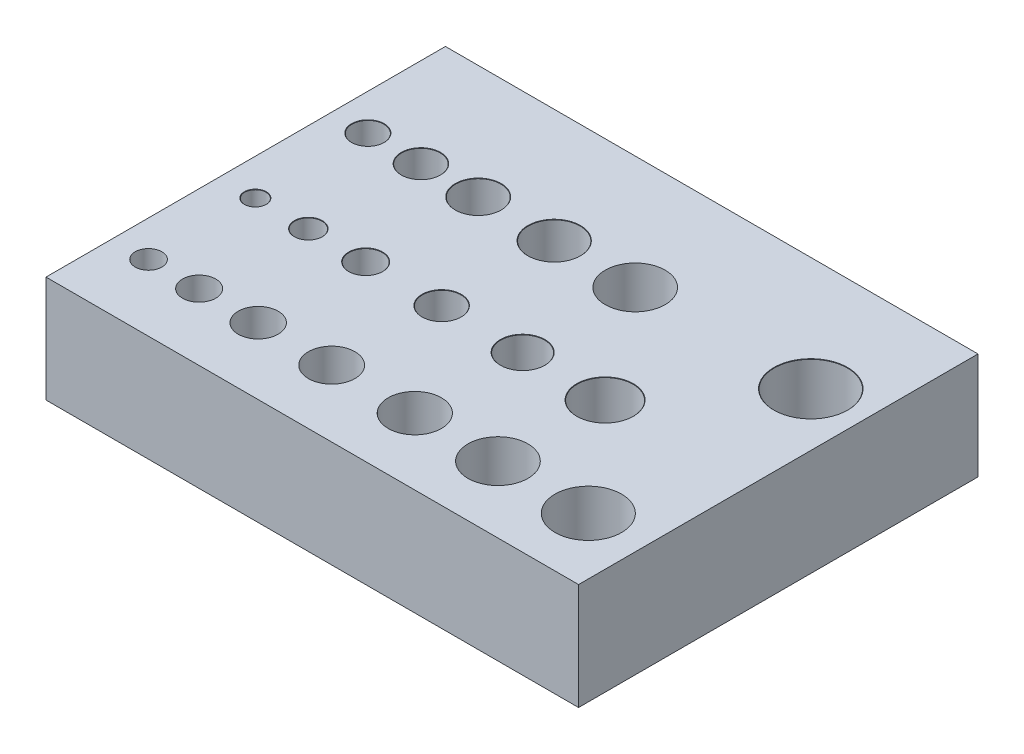
SolidWorks part; units mm, degrees
ref_plane "Front Plane" through (0, 0, 0) normal (0, 0, 1) x (1, 0, 0)
ref_plane "Top Plane" through (0, 0, 0) normal (0, 1, 0) x (1, 0, 0)
ref_plane "Right Plane" through (0, 0, 0) normal (1, 0, 0) x (0, 0, -1)
sketch "Sketch1" plane through (0, 0, 0) normal (0, 1, 0) x (1, 0, 0)
  line L0 (0, 5) -> (40, 5) construction
  line L1 (0, 0) -> (40, 0)
  line L2 (0, 0) -> (0, 30)
  line L3 (0, 30) -> (40, 30)
  line L4 (40, 0) -> (40, 30)
  line L5 (0, 12.8995) -> (40, 12.8995) construction
  circle A0 centre (2.7023, 5) radius 1
  circle A1 centre (6.5026, 5) radius 1.25
  circle A2 centre (10.9365, 5) radius 1.5
  circle A3 centre (16.457, 5) radius 1.75
  circle A4 centre (22.7004, 5) radius 2
  circle A5 centre (28.946, 5) radius 2.25
  circle A6 centre (35.7324, 5) radius 2.5
  point P19 (2.7023, 12.8995)
  point P22 (6.5026, 12.8995)
  point P23 (10.9365, 12.8995)
  point P24 (16.457, 12.8995)
  point P27 (22.7004, 12.8995)
  point P28 (28.946, 12.8995)
  point P29 (35.7324, 12.8995)
  dimension "D3" = 2
  dimension "D4" = 2.5
  dimension "D5" = 3
  dimension "D6" = 3.5
  dimension "D7" = 4
  dimension "D8" = 4.5
  dimension "D10" = 5
  dimension "D1" = 30
  dimension "D2" = 40
  dimension "D9" = 5
extrude "Boss-Extrude1" add sketch "Sketch1" along normal blind 8
sketch "Sketch2" plane through (0, 8, 0) normal (0, 1, 0) x (1, 0, 0)
  line L0 (0, 13) -> (40, 13) construction
  line L1 (0, 30) -> (0, 0) construction
  line L2 (40, 0) -> (40, 30) construction
  line L3 (0, 0) -> (40, 0) construction
  line L4 (0, 21.4534) -> (40, 21.4534) construction
  point P6 (2.7202, 13)
  point P7 (6.7037, 13)
  point P8 (11.0102, 13)
  point P9 (16.7163, 13)
  point P10 (22.7992, 13)
  point P11 (28.9898, 13)
  point P12 (35.9878, 13)
  point P17 (2.7202, 21.4534)
  point P18 (6.7037, 21.4534)
  point P19 (11.0102, 21.4534)
  point P20 (16.7163, 21.4534)
  point P21 (22.7992, 21.4534)
  point P22 (28.9898, 21.4534)
  point P23 (35.9878, 21.4534)
  dimension "D1" = 13
hole_wizard "Tap Drill for M2x0.4 Tap1" positions "Sketch3" profile "Sketch4" hole size "M2x0.4" standard "ANSI Metric" end condition through all
sketch "Sketch3" plane through (0, 8, 0) normal (0, 1, 0) x (1, 0, 0)
  point P0 (2.7202, 13)
sketch "Sketch4" plane through (2.7202, 8, -13) normal (1, 0, 0) x (0, 0, 1)
  line L0 (0, 0) -> (0, 8)
  line L1 (0, 8) -> (0.825, 8)
  line L2 (0.8, 7.975) -> (0.8, 0.025)
  line L3 (0.8, 0.025) -> (0.825, 0)
  line L5 (0.825, 0) -> (0, 0)
  line L6 (-0.8, 0.025) -> (-0.825, 0) construction
  line L7 (0.825, 8) -> (0.8, 7.975)
  line L8 (-0.825, 8) -> (-0.8, 7.975) construction
  line L11 (0, -6.35) -> (0, 107.95) construction
  dimension "Thru Hole Dia." = 1.6
  dimension "Thru Hole Depth" = 8
  dimension "Near C'Sink Dia." = 1.65
  dimension "Near C'Sink Angle" = 90
  dimension "Far C'Sink Dia." = 1.65
  dimension "Far C'Sink Angle" = 90
hole_wizard "Tap Drill for M2.5x0.45 Tap1" positions "Sketch5" profile "Sketch6" hole size "M2.5x0.45" standard "ANSI Metric" end condition through all
sketch "Sketch5" plane through (0, 8, 0) normal (0, 1, 0) x (1, 0, 0)
  point P0 (6.7037, 13)
sketch "Sketch6" plane through (6.7037, 8, -13) normal (1, 0, 0) x (0, 0, 1)
  line L0 (0, 0) -> (0, 8)
  line L1 (0, 8) -> (1.05, 8)
  line L2 (1.025, 7.975) -> (1.025, 0.025)
  line L3 (1.025, 0.025) -> (1.05, 0)
  line L5 (1.05, 0) -> (0, 0)
  line L6 (-1.025, 0.025) -> (-1.05, 0) construction
  line L7 (1.05, 8) -> (1.025, 7.975)
  line L8 (-1.05, 8) -> (-1.025, 7.975) construction
  line L11 (0, -6.35) -> (0, 107.95) construction
  dimension "Thru Hole Dia." = 2.05
  dimension "Thru Hole Depth" = 8
  dimension "Near C'Sink Dia." = 2.1
  dimension "Near C'Sink Angle" = 90
  dimension "Far C'Sink Dia." = 2.1
  dimension "Far C'Sink Angle" = 90
hole_wizard "Tap Drill for M3x0.5 Tap1" positions "Sketch7" profile "Sketch8" hole size "M3x0.5" standard "ANSI Metric" end condition through all
sketch "Sketch7" plane through (0, 8, 0) normal (0, 1, 0) x (1, 0, 0)
  point P0 (11.0102, 13)
sketch "Sketch8" plane through (11.0102, 8, -13) normal (1, 0, 0) x (0, 0, 1)
  line L0 (0, 0) -> (0, 8)
  line L1 (0, 8) -> (1.275, 8)
  line L2 (1.25, 7.975) -> (1.25, 0.025)
  line L3 (1.25, 0.025) -> (1.275, 0)
  line L5 (1.275, 0) -> (0, 0)
  line L6 (-1.25, 0.025) -> (-1.275, 0) construction
  line L7 (1.275, 8) -> (1.25, 7.975)
  line L8 (-1.275, 8) -> (-1.25, 7.975) construction
  line L11 (0, -6.35) -> (0, 107.95) construction
  dimension "Thru Hole Dia." = 2.5
  dimension "Thru Hole Depth" = 8
  dimension "Near C'Sink Dia." = 2.55
  dimension "Near C'Sink Angle" = 90
  dimension "Far C'Sink Dia." = 2.55
  dimension "Far C'Sink Angle" = 90
hole_wizard "Tap Drill for M3.5x0.6 Tap1" positions "Sketch9" profile "Sketch10" hole size "M3.5x0.6" standard "ANSI Metric" end condition through all
sketch "Sketch9" plane through (0, 8, 0) normal (0, 1, 0) x (1, 0, 0)
  point P0 (16.7163, 13)
sketch "Sketch10" plane through (16.7163, 8, -13) normal (1, 0, 0) x (0, 0, 1)
  line L0 (0, 0) -> (0, 8)
  line L1 (0, 8) -> (1.475, 8)
  line L2 (1.45, 7.975) -> (1.45, 0.025)
  line L3 (1.45, 0.025) -> (1.475, 0)
  line L5 (1.475, 0) -> (0, 0)
  line L6 (-1.45, 0.025) -> (-1.475, 0) construction
  line L7 (1.475, 8) -> (1.45, 7.975)
  line L8 (-1.475, 8) -> (-1.45, 7.975) construction
  line L11 (0, -6.35) -> (0, 107.95) construction
  dimension "Thru Hole Dia." = 2.9
  dimension "Thru Hole Depth" = 8
  dimension "Near C'Sink Dia." = 2.95
  dimension "Near C'Sink Angle" = 90
  dimension "Far C'Sink Dia." = 2.95
  dimension "Far C'Sink Angle" = 90
hole_wizard "Tap Drill for M4x0.7 Tap1" positions "Sketch11" profile "Sketch12" hole size "M4x0.7" standard "ANSI Metric" end condition through all
sketch "Sketch11" plane through (0, 8, 0) normal (0, 1, 0) x (1, 0, 0)
  point P0 (22.7992, 13)
sketch "Sketch12" plane through (22.7992, 8, -13) normal (1, 0, 0) x (0, 0, 1)
  line L0 (0, 0) -> (0, 8)
  line L1 (0, 8) -> (1.675, 8)
  line L2 (1.65, 7.975) -> (1.65, 0.025)
  line L3 (1.65, 0.025) -> (1.675, 0)
  line L5 (1.675, 0) -> (0, 0)
  line L6 (-1.65, 0.025) -> (-1.675, 0) construction
  line L7 (1.675, 8) -> (1.65, 7.975)
  line L8 (-1.675, 8) -> (-1.65, 7.975) construction
  line L11 (0, -6.35) -> (0, 107.95) construction
  dimension "Thru Hole Dia." = 3.3
  dimension "Thru Hole Depth" = 8
  dimension "Near C'Sink Dia." = 3.35
  dimension "Near C'Sink Angle" = 90
  dimension "Far C'Sink Dia." = 3.35
  dimension "Far C'Sink Angle" = 90
hole_wizard "Tap Drill for M5x0.8 Tap1" positions "Sketch13" profile "Sketch14" hole size "M5x0.8" standard "ANSI Metric" end condition through all
sketch "Sketch13" plane through (0, 8, 0) normal (0, 1, 0) x (1, 0, 0)
  point P0 (28.9898, 13)
sketch "Sketch14" plane through (28.9898, 8, -13) normal (1, 0, 0) x (0, 0, 1)
  line L0 (0, 0) -> (0, 8)
  line L1 (0, 8) -> (2.125, 8)
  line L2 (2.1, 7.975) -> (2.1, 0.025)
  line L3 (2.1, 0.025) -> (2.125, 0)
  line L5 (2.125, 0) -> (0, 0)
  line L6 (-2.1, 0.025) -> (-2.125, 0) construction
  line L7 (2.125, 8) -> (2.1, 7.975)
  line L8 (-2.125, 8) -> (-2.1, 7.975) construction
  line L11 (0, -6.35) -> (0, 107.95) construction
  dimension "Thru Hole Dia." = 4.2
  dimension "Thru Hole Depth" = 8
  dimension "Near C'Sink Dia." = 4.25
  dimension "Near C'Sink Angle" = 90
  dimension "Far C'Sink Dia." = 4.25
  dimension "Far C'Sink Angle" = 90
hole_wizard "M2 Clearance Hole1" positions "Sketch15" profile "Sketch16" hole size "M2" standard "ANSI Metric" end condition through all
sketch "Sketch15" plane through (0, 8, 0) normal (0, 1, 0) x (1, 0, 0)
  point P0 (2.7202, 21.4534)
sketch "Sketch16" plane through (2.7202, 8, -21.4534) normal (1, 0, 0) x (0, 0, 1)
  line L0 (0, 0) -> (0, 8)
  line L1 (0, 8) -> (1.225, 8)
  line L2 (1.2, 7.975) -> (1.2, 0.025)
  line L3 (1.2, 0.025) -> (1.225, 0)
  line L5 (1.225, 0) -> (0, 0)
  line L6 (-1.2, 0.025) -> (-1.225, 0) construction
  line L7 (1.225, 8) -> (1.2, 7.975)
  line L8 (-1.225, 8) -> (-1.2, 7.975) construction
  line L11 (0, -6.35) -> (0, 107.95) construction
  dimension "Thru Hole Dia." = 2.4
  dimension "Thru Hole Depth" = 8
  dimension "Near C'Sink Dia." = 2.45
  dimension "Near C'Sink Angle" = 90
  dimension "Far C'Sink Dia." = 2.45
  dimension "Far C'Sink Angle" = 90
hole_wizard "M2.5 Clearance Hole1" positions "Sketch17" profile "Sketch18" hole size "M2.5" standard "ANSI Metric" end condition through all
sketch "Sketch17" plane through (0, 8, 0) normal (0, 1, 0) x (1, 0, 0)
  point P0 (6.7037, 21.4534)
sketch "Sketch18" plane through (6.7037, 8, -21.4534) normal (1, 0, 0) x (0, 0, 1)
  line L0 (0, 0) -> (0, 8)
  line L1 (0, 8) -> (1.475, 8)
  line L2 (1.45, 7.975) -> (1.45, 0.025)
  line L3 (1.45, 0.025) -> (1.475, 0)
  line L5 (1.475, 0) -> (0, 0)
  line L6 (-1.45, 0.025) -> (-1.475, 0) construction
  line L7 (1.475, 8) -> (1.45, 7.975)
  line L8 (-1.475, 8) -> (-1.45, 7.975) construction
  line L11 (0, -6.35) -> (0, 107.95) construction
  dimension "Thru Hole Dia." = 2.9
  dimension "Thru Hole Depth" = 8
  dimension "Near C'Sink Dia." = 2.95
  dimension "Near C'Sink Angle" = 90
  dimension "Far C'Sink Dia." = 2.95
  dimension "Far C'Sink Angle" = 90
hole_wizard "M3 Clearance Hole1" positions "Sketch19" profile "Sketch20" hole size "M3" standard "ANSI Metric" end condition through all
sketch "Sketch19" plane through (0, 8, 0) normal (0, 1, 0) x (1, 0, 0)
  point P0 (11.0102, 21.4534)
sketch "Sketch20" plane through (11.0102, 8, -21.4534) normal (1, 0, 0) x (0, 0, 1)
  line L0 (0, 0) -> (0, 8)
  line L1 (0, 8) -> (1.725, 8)
  line L2 (1.7, 7.975) -> (1.7, 0.025)
  line L3 (1.7, 0.025) -> (1.725, 0)
  line L5 (1.725, 0) -> (0, 0)
  line L6 (-1.7, 0.025) -> (-1.725, 0) construction
  line L7 (1.725, 8) -> (1.7, 7.975)
  line L8 (-1.725, 8) -> (-1.7, 7.975) construction
  line L11 (0, -6.35) -> (0, 107.95) construction
  dimension "Thru Hole Dia." = 3.4
  dimension "Thru Hole Depth" = 8
  dimension "Near C'Sink Dia." = 3.45
  dimension "Near C'Sink Angle" = 90
  dimension "Far C'Sink Dia." = 3.45
  dimension "Far C'Sink Angle" = 90
hole_wizard "M3.5 Clearance Hole1" positions "Sketch21" profile "Sketch22" hole size "M3.5" standard "ANSI Metric" end condition through all
sketch "Sketch21" plane through (0, 8, 0) normal (0, 1, 0) x (1, 0, 0)
  point P0 (16.7163, 21.4534)
sketch "Sketch22" plane through (16.7163, 8, -21.4534) normal (1, 0, 0) x (0, 0, 1)
  line L0 (0, 0) -> (0, 8)
  line L1 (0, 8) -> (1.975, 8)
  line L2 (1.95, 7.975) -> (1.95, 0.025)
  line L3 (1.95, 0.025) -> (1.975, 0)
  line L5 (1.975, 0) -> (0, 0)
  line L6 (-1.95, 0.025) -> (-1.975, 0) construction
  line L7 (1.975, 8) -> (1.95, 7.975)
  line L8 (-1.975, 8) -> (-1.95, 7.975) construction
  line L11 (0, -6.35) -> (0, 107.95) construction
  dimension "Thru Hole Dia." = 3.9
  dimension "Thru Hole Depth" = 8
  dimension "Near C'Sink Dia." = 3.95
  dimension "Near C'Sink Angle" = 90
  dimension "Far C'Sink Dia." = 3.95
  dimension "Far C'Sink Angle" = 90
hole_wizard "M4 Clearance Hole1" positions "Sketch23" profile "Sketch24" hole size "M4" standard "ANSI Metric" end condition through all
sketch "Sketch23" plane through (0, 8, 0) normal (0, 1, 0) x (1, 0, 0)
  point P0 (22.7992, 21.4534)
sketch "Sketch24" plane through (22.7992, 8, -21.4534) normal (1, 0, 0) x (0, 0, 1)
  line L0 (0, 0) -> (0, 8)
  line L1 (0, 8) -> (2.25, 8)
  line L2 (2.25, 8) -> (2.25, 0)
  line L5 (2.25, 0) -> (0, 0)
  line L11 (0, -6.35) -> (0, 107.95) construction
  dimension "Thru Hole Dia." = 4.5
  dimension "Thru Hole Depth" = 8
hole_wizard "M5 Clearance Hole1" positions "Sketch25" profile "Sketch26" hole size "M5" standard "ANSI Metric" end condition through all
sketch "Sketch25" plane through (0, 8, 0) normal (0, 1, 0) x (1, 0, 0)
  point P0 (35.9878, 21.4534)
sketch "Sketch26" plane through (35.9878, 8, -21.4534) normal (1, 0, 0) x (0, 0, 1)
  line L0 (0, 0) -> (0, 8)
  line L1 (0, 8) -> (2.775, 8)
  line L2 (2.75, 7.975) -> (2.75, 0.025)
  line L3 (2.75, 0.025) -> (2.775, 0)
  line L5 (2.775, 0) -> (0, 0)
  line L6 (-2.75, 0.025) -> (-2.775, 0) construction
  line L7 (2.775, 8) -> (2.75, 7.975)
  line L8 (-2.775, 8) -> (-2.75, 7.975) construction
  line L11 (0, -6.35) -> (0, 107.95) construction
  dimension "Thru Hole Dia." = 5.5
  dimension "Thru Hole Depth" = 8
  dimension "Near C'Sink Dia." = 5.55
  dimension "Near C'Sink Angle" = 90
  dimension "Far C'Sink Dia." = 5.55
  dimension "Far C'Sink Angle" = 90
sketch "Sketch27" plane through (0, 0, -30) normal (0, 0, -1) x (-1, 0, 0)
  circle A0 centre (-27.945, 3.8336) radius 1.5
  dimension "D1" = 3
extrude "Cut-Extrude1" cut sketch "Sketch27" against normal blind 5
